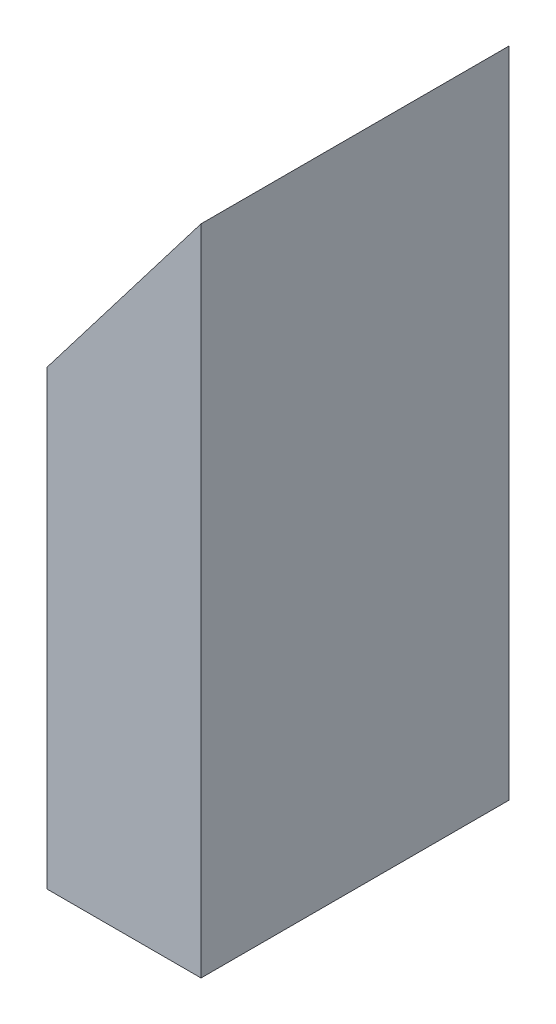
SolidWorks part; units mm, degrees
material "Brass"
ref_plane "Front Plane" through (0, 0, 0) normal (0, 0, 1) x (1, 0, 0)
ref_plane "Top Plane" through (0, 0, 0) normal (0, 1, 0) x (1, 0, 0)
ref_plane "Right Plane" through (0, 0, 0) normal (1, 0, 0) x (0, 0, -1)
sketch "Sketch1" plane through (0, 0, 0) normal (0, 0, 1) x (1, 0, 0)
  line L0 (-1028.7422, -11.9908) -> (48971.2578, -11.9908) construction
  line L1 (-1034.7163, 13.4092) -> (48965.2837, 13.4092) construction
  line L2 (-638.3981, -780.6873) -> (29751.1874, 38924.1372) construction
  line L3 (-30.6064, 13.4092) -> (-32.501, 14.8593) construction
  line L4 (-15.1685, 33.5793) -> (-17.0631, 35.0294) construction
  line L5 (-15.1685, 33.5793) -> (-15.1685, -11.9908) construction
  line L6 (-21.5212, 25.2793) -> (-24.3658, 27.4565) construction
  line L7 (-8.8158, 41.8792) -> (-11.6604, 44.0564) construction
  line L8 (-21.5212, 25.2793) -> (-21.5212, -11.9908) construction
  line L9 (-8.8158, 41.8792) -> (-8.8158, -11.9908) construction
  line L10 (-8.8158, 41.8792) -> (-21.5212, 25.2793)
  line L11 (-21.5212, 25.2793) -> (-21.5212, -11.9908)
  line L12 (-21.5212, -11.9908) -> (-8.8158, -11.9908)
  line L13 (-8.8158, -11.9908) -> (-8.8158, 41.8792)
  dimension "D1" = 25.4
  dimension "D2" = 25.4
  dimension "D3" = 20.9042
  dimension "D4" = 10.4521
  dimension "D5" = 37.43
extrude "Extrude1" add sketch "Sketch1" along normal blind 25.4
hole_wizard "1/4-20 Tapped Hole2" positions "Sketch6" profile "Sketch7" tap size "1/4-20" standard "Ansi Inch"
sketch "Sketch6" plane through (7.2003, -11.9908, 18.0613) normal (0, -1, 0) x (-1, 0, 0)
  point P0 (22.9291, 5.3613)
sketch "Sketch7" plane through (-15.7288, -11.9908, 12.7) normal (1, 0, 0) x (0, 0, -1)
  line L0 (0, 0) -> (0, 17.5358)
  line L1 (0, 17.5358) -> (2.5527, 16.002)
  line L2 (2.5527, 16.002) -> (2.5527, 0)
  line L3 (2.5527, 0) -> (0, 0)
  line L4 (0, 17.5358) -> (-2.5527, 16.002) construction
  line L5 (0, -6.35) -> (0, 107.95) construction
  dimension "Tap Drill Dia." = 5.1054
  dimension "Tap Drill Depth" = 16.002
  dimension "Drill Angle" = 118
cosmetic thread "Hole Thread2" parameters "D1"=9.525, "D2"=6.35
